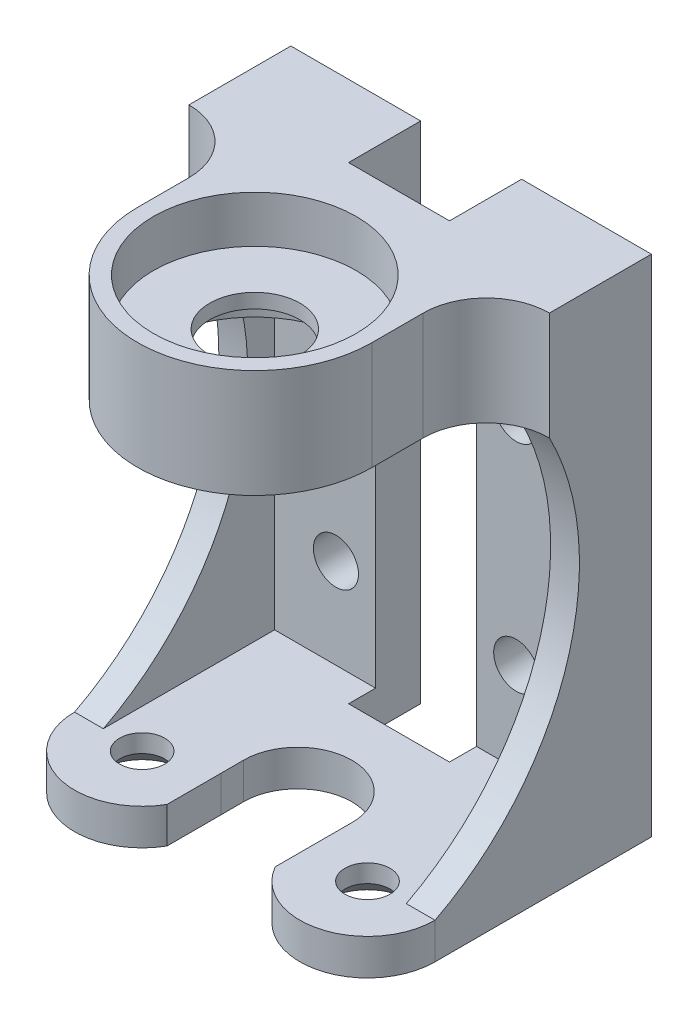
SolidWorks part; units mm, degrees
ref_plane "Front Plane" through (0, 0, 0) normal (0, 0, 1) x (1, 0, 0)
ref_plane "Top Plane" through (0, 0, 0) normal (0, 1, 0) x (1, 0, 0)
ref_plane "Right Plane" through (0, 0, 0) normal (1, 0, 0) x (0, 0, -1)
sketch "Sketch1" plane through (0, 0, 0) normal (0, 0, 1) x (1, 0, 0)
  line L0 (0, 29.21) -> (0, -6.35) construction
  line L1 (-12.7, 29.21) -> (12.7, 29.21)
  line L2 (-12.7, 29.21) -> (-12.7, -6.35)
  line L3 (-12.7, -6.35) -> (12.7, -6.35)
  line L4 (12.7, 29.21) -> (12.7, -6.35)
  line L5 (0, 10.16) -> (23.122, 10.16) construction
  circle A0 centre (-6.35, 2.54) radius 1.5875
  circle A1 centre (6.35, 2.54) radius 1.5875
  circle A2 centre (6.35, 17.78) radius 1.5875
  circle A3 centre (-6.35, 17.78) radius 1.5875
  point P0 (0, 0)
  dimension "D7" = 3.175
  dimension "D8" = 3.175
  dimension "D2" = 35.56
  dimension "D4" = 12.7
  dimension "D1" = 12.7
  dimension "D3" = 12.7
  dimension "D5" = 6.35
  dimension "D6" = 6.35
  dimension "D9" = 8.89
  dimension "D10" = 8.89
  dimension "D11" = 11.43
extrude "Boss-Extrude1" add sketch "Sketch1" along normal blind 3.175
sketch "Sketch7" plane through (0, 0, 3.175) normal (0, 0, 1) x (1, 0, 0)
  line L0 (0, -2.6536) -> (0, 2.4264) construction
  line L1 (-12.7, -3.81) -> (12.7, -3.81)
  line L2 (-12.7, -3.81) -> (-12.7, -6.35)
  line L3 (-12.7, -6.35) -> (12.7, -6.35)
  line L4 (12.7, -3.81) -> (12.7, -6.35)
  line L5 (-12.7, -3.81) -> (12.7, -6.35) construction
  line L6 (-12.7, -6.35) -> (12.7, -3.81) construction
  line L7 (-12.7, -6.35) -> (12.7, -6.35) construction
  line L8 (12.7, -6.35) -> (12.7, 29.21) construction
  line L9 (-12.7, 21.59) -> (12.7, 21.59)
  line L10 (-12.7, 21.59) -> (-12.7, 29.21)
  line L11 (-12.7, 29.21) -> (12.7, 29.21)
  line L12 (12.7, 21.59) -> (12.7, 29.21)
  line L13 (-12.7, 21.59) -> (12.7, 29.21) construction
  line L14 (-12.7, 29.21) -> (12.7, 21.59) construction
  line L15 (12.7, 29.21) -> (-12.7, 29.21) construction
  point P0 (0, -5.08)
  point P7 (0, 25.4)
  dimension "D1" = 2.54
  dimension "D2" = 7.62
  dimension "1" = 25.4
  dimension "D3" = 3.81
  dimension "D4" = 25.4
extrude "Boss-Extrude3" add sketch "Sketch7" along normal blind 20.32
sketch "Sketch11" plane through (0, -6.35, 0) normal (0, -1, 0) x (1, 0, 0)
  line L0 (12.7, 23.495) -> (12.7, 0) construction
  line L1 (-3.8147, 12.219) -> (-3.81, 13.806)
  line L2 (-12.7, 15.24) -> (12.7, 15.24) construction
  line L3 (3.8147, 12.219) -> (3.81, 13.806)
  line L4 (-12.7, 23.495) -> (12.7, 23.495) construction
  line L5 (-12.7, 23.495) -> (-12.7, 0) construction
  line L7 (0, 23.495) -> (0, 12.219) construction
  line L8 (3.81, 17.616) -> (3.81, 13.806)
  line L9 (-12.7, 23.495) -> (12.7, 23.495) construction
  line L10 (-3.81, 17.616) -> (-3.81, 13.806)
  circle A0 centre (-7.9375, 15.24) radius 1.5875
  circle A1 centre (7.9375, 15.24) radius 1.5875
  arc A2 (12.7, 15.24) -> (3.81, 17.616) centre (7.9375, 15.24) ccw
  arc A4 (-3.8146, 12.2415) -> (3.8146, 12.2415) centre (0, 12.219) ccw
  arc A5 (-12.7, 15.24) -> (-3.81, 17.616) centre (-7.9375, 15.24) cw
  point P17 (-12.3447, 26.9875)
  point P26 (12.3447, 26.9875)
  dimension "D3" = 1.587
  dimension "D2" = 3.8147
  dimension "D5" = 3.175
  dimension "D6" = 4.7625
  dimension "D1" = 8.89
  dimension "D8" = 1.587
  dimension "D9" = 3.81
  dimension "D10" = 11.276
extrude "Cut-Extrude1" cut sketch "Sketch11" against normal blind 10
chamfer "Chamfer2" distance 1.27 angle 45 2 edges at (9.525, -6.35, 15.24) (-6.35, -6.35, 15.24)
sketch "Sketch13" plane through (0, 29.21, 0) normal (0, 1, 0) x (1, 0, 0)
  line L0 (12.7, 0) -> (-12.7, 0) construction
  line L1 (12.7, -23.495) -> (12.7, 0) construction
  circle A0 centre (0, -15.24) radius 3.175
  dimension "D1" = 6.35
  dimension "D2" = 15.24
  dimension "D3" = 12.7
extrude "Cut-Extrude2" cut sketch "Sketch13" against normal blind 12.7
sketch "Sketch14" plane through (0, 29.21, 0) normal (0, 1, 0) x (1, 0, 0)
  circle A0 centre (0, -15.24) radius 7.1438
  circle A1 centre (0, -15.24) radius 3.175 construction
  dimension "D1" = 14.2875
extrude "Cut-Extrude3" cut sketch "Sketch14" against normal blind 3.302
sketch "Sketch15" plane through (0, 21.59, 0) normal (0, -1, 0) x (1, 0, 0)
  circle A0 centre (0, 15.24) radius 7.1438
  circle A1 centre (0, 15.24) radius 3.175 construction
  dimension "D1" = 14.2875
extrude "Cut-Extrude4" cut sketch "Sketch15" against normal blind 3.302
sketch "Sketch16" plane through (0, 29.21, 0) normal (0, 1, 0) x (1, 0, 0)
  line L0 (-8.255, -15.24) -> (-8.255, -11.6294)
  line L2 (8.255, -15.24) -> (8.255, -11.6294)
  line L3 (-12.7, -23.495) -> (-12.7, 0) construction
  line L4 (12.7, -23.495) -> (12.7, 0) construction
  line L5 (12.7, -7.1844) -> (12.7, -23.495)
  line L6 (12.7, -23.495) -> (-12.7, -23.495)
  line L7 (-12.7, -23.495) -> (-12.7, -7.1844)
  line L8 (12.7, 0) -> (-12.7, 0) construction
  arc A0 (-8.255, -15.24) -> (8.255, -15.24) centre (0, -15.24) ccw
  arc A1 (-8.255, -11.6294) -> (-12.7, -7.1844) centre (-12.7, -11.6294) ccw
  arc A2 (12.7, -7.1844) -> (8.255, -11.6294) centre (12.7, -11.6294) ccw
  line M3 (-12.7, 0) -> (-12.7, -23.495)
  line M4 (-12.7, -23.495) -> (12.7, -23.495)
  line M5 (12.7, -23.495) -> (12.7, 0)
  dimension "D1" = 8.255
  dimension "D2" = 11.6294
  dimension "D3" = 11.6294
extrude "Cut-Extrude5" cut sketch "Sketch16" against normal blind 12.7 contours A2 L2 A0 L6 M5 | L0 A1 A0 M3 M4
sketch "Sketch17" plane through (0, 0, 3.175) normal (0, 0, 1) x (1, 0, 0)
  line L0 (12.7, -3.81) -> (-12.7, -3.81) construction
  line L1 (12.7, 21.59) -> (10.671, 21.59)
  line L2 (12.7, 21.59) -> (12.7, -3.81)
  line L3 (12.7, -3.81) -> (10.671, -3.81)
  line L4 (10.671, 21.59) -> (10.671, -3.81)
  line L5 (0, 0) -> (0, 8.4961) construction
  line L6 (-10.671, 21.59) -> (-10.671, -3.81)
  line M4 (12.7, -3.81) -> (12.7, 21.59)
  line M5 (12.7, 21.59) -> (-12.7, 21.59)
  line M6 (-12.7, 21.59) -> (-12.7, -3.81)
  line M7 (-12.7, -3.81) -> (12.7, -3.81)
  dimension "D1" = 2.029
  dimension "D2" = 10.671
extrude "Boss-Extrude4" add sketch "Sketch17" along normal blind 12.7 contours L6 M5 M6 M7 | L4 M5 M7 M4
sketch "Sketch18" plane through (12.7, 0, 0) normal (1, 0, 0) x (0, 0, -1)
  arc A0 (-7.1844, 21.59) -> (-15.24, -3.81) centre (-23.9122, 12.9178) cw
  line M2 (-7.1844, 21.59) -> (-15.875, 21.59)
  line M3 (-15.875, 21.59) -> (-15.875, -3.81)
  line M4 (-15.875, -3.81) -> (-15.24, -3.81)
  dimension "D1" = 18.8421
extrude "Cut-Extrude6" cut sketch "Sketch18" against normal through all contours A0 M2 M3 M4
sketch "Sketch19" plane through (0, 29.21, 0) normal (0, 1, 0) x (1, 0, 0)
  line L1 (3.556, 0) -> (-3.556, 0)
  line L2 (3.556, 0) -> (3.556, -5.08)
  line L3 (3.556, -5.08) -> (-3.556, -5.08)
  line L4 (-3.556, 0) -> (-3.556, -5.08)
  line L5 (3.556, 0) -> (-3.556, -5.08) construction
  line L6 (3.556, -5.08) -> (-3.556, 0) construction
  line L7 (12.7, 0) -> (-12.7, 0) construction
  line L8 (-12.7, -7.1844) -> (-12.7, 0) construction
  dimension "D1" = 5.08
  dimension "D2" = 0
  dimension "D3" = 7.112
  dimension "D4" = 9.144
extrude "Cut-Extrude7" cut sketch "Sketch19" against normal through all
equation "\"D4@Sketch19\"=.5-\"D3@Sketch19\"/2"
equation "\"D9@Sketch1\"=\"D2@Sketch1\"/4"
